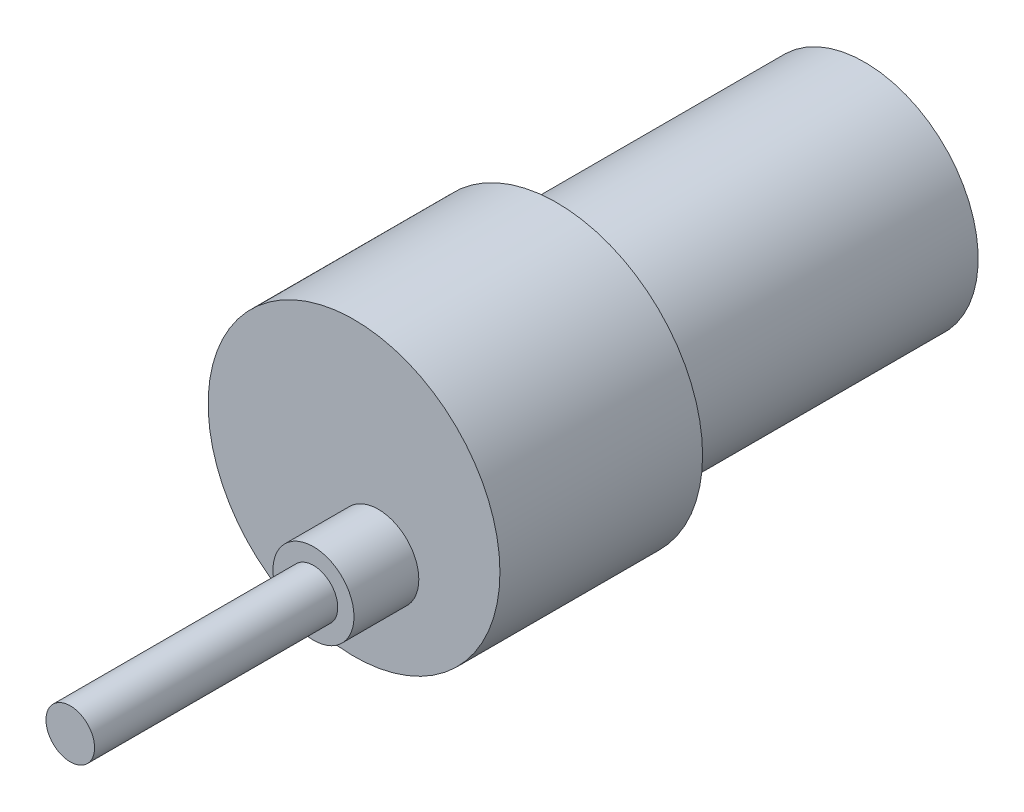
SolidWorks part; units mm, degrees
ref_plane "Front Plane" through (0, 0, 0) normal (0, 0, 1) x (1, 0, 0)
ref_plane "Top Plane" through (0, 0, 0) normal (0, 1, 0) x (1, 0, 0)
ref_plane "Right Plane" through (0, 0, 0) normal (1, 0, 0) x (0, 0, -1)
sketch "Sketch1" plane through (0, 0, 0) normal (0, 0, 1) x (1, 0, 0)
  circle A0 centre (0, 0) radius 18
  dimension "D1" = 36
extrude "Boss-Extrude1" add sketch "Sketch1" along normal blind 25
sketch "Sketch2" plane through (0, 0, 0) normal (0, 0, -1) x (-1, 0, 0)
  circle A0 centre (0, 0) radius 14
  dimension "D1" = 28
extrude "Boss-Extrude2" add sketch "Sketch2" along normal blind 38
sketch "Sketch3" plane through (0, 0, -38) normal (0, 0, -1) x (-1, 0, 0)
  circle A0 centre (0, 0) radius 5
  dimension "D1" = 10
extrude "Boss-Extrude3" add sketch "Sketch3" along normal blind 2
sketch "Sketch4" plane through (0, 0, 25) normal (0, 0, 1) x (1, 0, 0)
  circle A0 centre (0, 0) radius 11.5
  circle A1 centre (2.9916, -5.7706) radius 5
  dimension "D1" = 23
  dimension "D2" = 10
extrude "Boss-Extrude4" add sketch "Sketch4" along normal blind 8 contours A1
sketch "Sketch5" plane through (0, 0, 33) normal (0, 0, 1) x (1, 0, 0)
  circle A0 centre (2.9916, -5.7706) radius 3
  dimension "D1" = 6
extrude "Boss-Extrude5" add sketch "Sketch5" along normal blind 30
